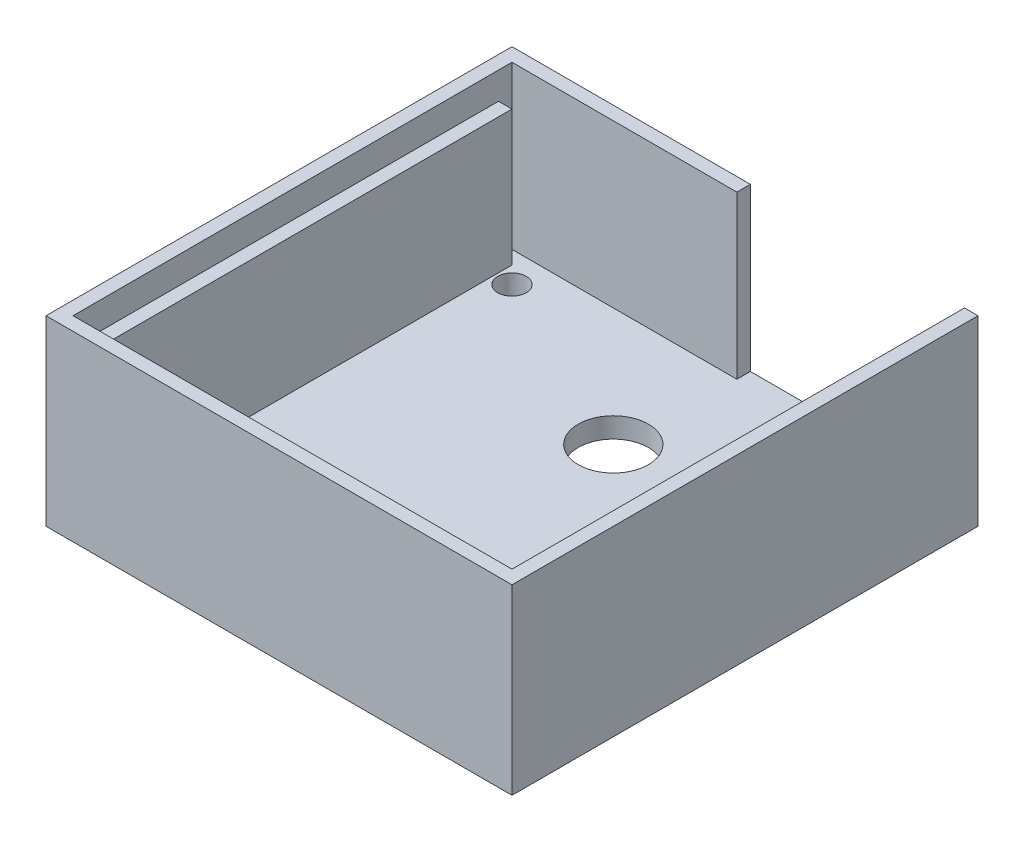
SolidWorks part; units mm, degrees
ref_plane "前视基准面" through (0, 0, 0) normal (0, 0, 1) x (1, 0, 0)
ref_plane "上视基准面" through (0, 0, 0) normal (0, 1, 0) x (1, 0, 0)
ref_plane "右视基准面" through (0, 0, 0) normal (1, 0, 0) x (0, 0, -1)
sketch "草图1" plane through (0, 0, 0) normal (0, 1, 0) x (1, 0, 0)
  line L1 (0, 0) -> (34.5, 0)
  line L2 (0, 0) -> (0, 34.5)
  line L3 (0, 34.5) -> (34.5, 34.5)
  line L4 (34.5, 0) -> (34.5, 34.5)
  dimension "D1" = 34.5
  dimension "D2" = 34.5
extrude "凸台-拉伸1" add sketch "草图1" along normal blind 13.5
sketch "草图2" plane through (0, 13.5, 0) normal (0, 1, 0) x (1, 0, 0)
  line L0 (17.25, 34.5) -> (17.25, -5.1184) construction
  line L1 (34.5, 34.5) -> (0, 34.5) construction
  line L2 (0, 17.25) -> (37.82, 17.25) construction
  line L3 (0, 34.5) -> (0, 0) construction
  line L16 (1, 33.5) -> (1, 1)
  line L17 (1, 1) -> (33.5, 1)
  line L18 (33.5, 1) -> (33.5, 33.5)
  line L19 (33.5, 33.5) -> (1, 33.5)
  dimension "D2" = 32.5
  dimension "D1" = 32.5
extrude "切除-拉伸1" cut sketch "草图2" against normal blind 2
sketch "草图3" plane through (0, 11.5, 0) normal (0, 1, 0) x (1, 0, 0)
  line L0 (17.25, 33.5) -> (17.25, 9.2832) construction
  line L1 (33.5, 33.5) -> (1, 33.5) construction
  line L2 (1, 17.25) -> (31.2686, 17.25) construction
  line L3 (1, 33.5) -> (1, 1) construction
  line L4 (33.5, 1) -> (33.5, 33.5) construction
  line L5 (2, 2) -> (32.5, 2)
  line L6 (2, 2) -> (2, 32.5)
  line L7 (2, 32.5) -> (32.5, 32.5)
  line L8 (32.5, 2) -> (32.5, 32.5)
  line L9 (2, 2) -> (32.5, 32.5) construction
  line L10 (2, 32.5) -> (32.5, 2) construction
  line L11 (33.5, 33.5) -> (1, 33.5) construction
  point P8 (17.25, 17.25)
  dimension "D1" = 1
  dimension "D2" = 1
extrude "切除-拉伸2" cut sketch "草图3" against normal offset from surface (10 mm away) 1.5 up to face at (17.25, 0, -17.25)
sketch "草图4" plane through (0, 1.5, 0) normal (0, 1, 0) x (1, 0, 0)
  line L0 (17.25, 32.5) -> (17.25, 2) construction
  line L1 (32.5, 32.5) -> (2, 32.5) construction
  line L2 (2, 2) -> (32.5, 2) construction
  line L3 (2, 17.25) -> (32.5, 17.25) construction
  line L4 (2, 32.5) -> (2, 2) construction
  line L5 (32.5, 2) -> (32.5, 32.5) construction
  circle A0 centre (3.25, 31.25) radius 1.0553
  circle A1 centre (31.25, 31.25) radius 1.0553
  circle A2 centre (31.25, 3.25) radius 1.0553
  circle A3 centre (3.25, 3.25) radius 1.0553
  circle A4 centre (17.25, 24.75) radius 2.6
  circle A5 centre (17.25, 9.75) radius 2.6
  dimension "D1" = 28
  dimension "D2" = 28
  dimension "D3" = 5.2
  dimension "D4" = 15
extrude "切除-拉伸3" cut sketch "草图4" against normal blind 12
sketch "草图5" plane through (0, 13.5, 0) normal (0, 1, 0) x (1, 0, 0)
  line L1 (17.65, 34.5) -> (33.5, 34.5)
  line L2 (17.65, 34.5) -> (17.65, 32.484)
  line L3 (17.65, 32.484) -> (33.5, 32.484)
  line L4 (33.5, 34.5) -> (33.5, 32.484)
  line L6 (33.5, 1) -> (33.5, 33.5) construction
  point P4 (33.5, 32.484)
  dimension "D1" = 15.85
extrude "切除-拉伸4" cut sketch "草图5" against normal up to surface (12 mm away) up to face at (31.25, 1.5, -32.3053)
sketch "草图7" plane through (0, 11.5, 0) normal (0, 1, 0) x (1, 0, 0)
  line L0 (1, 33.5) -> (1, 1) construction
  line L1 (17.65, 32.5) -> (1, 32.5)
  line L2 (17.65, 32.5) -> (17.65, 33.5)
  line L3 (17.65, 33.5) -> (1, 33.5)
  line L4 (1, 32.5) -> (1, 33.5)
  line L5 (1, 33.5) -> (1, 1) construction
extrude "切除-拉伸6" cut sketch "草图7" against normal blind 10
sketch "草图8" plane through (0, 11.5, 0) normal (0, 1, 0) x (1, 0, 0)
  line L0 (2, 2) -> (32.5, 2) construction
  line L1 (14.5, 2) -> (5, 2)
  line L2 (14.5, 2) -> (14.5, 1)
  line L3 (14.5, 1) -> (5, 1)
  line L4 (5, 2) -> (5, 1)
  line L5 (1, 1) -> (33.5, 1) construction
  line L6 (1, 32.5) -> (1, 1) construction
  dimension "D1" = 9.5
  dimension "D2" = 13.5
extrude "切除-拉伸7" cut sketch "草图8" against normal blind 10
